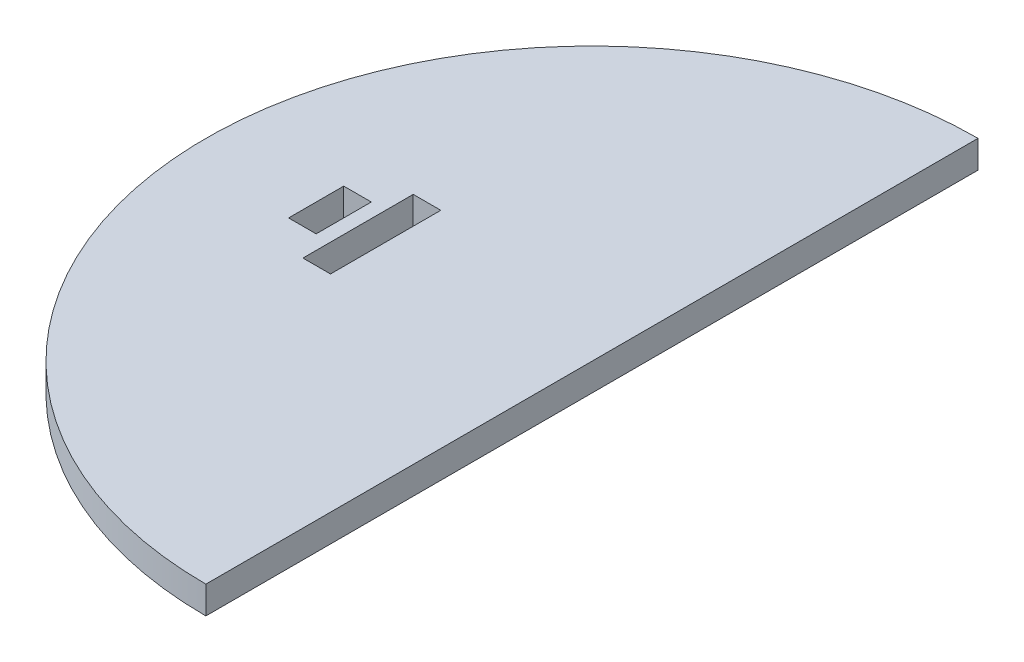
SolidWorks part; units mm, degrees
ref_plane "Front Plane" through (0, 0, 0) normal (0, 0, 1) x (1, 0, 0)
ref_plane "Top Plane" through (0, 0, 0) normal (0, 1, 0) x (1, 0, 0)
ref_plane "Right Plane" through (0, 0, 0) normal (1, 0, 0) x (0, 0, -1)
sketch "Sketch1" plane through (0, 0, 0) normal (0, 1, 0) x (1, 0, 0)
  line L0 (0, 70) -> (0, -70)
  line L2 (-50, -5) -> (-45, -5)
  line L3 (-50, -5) -> (-50, 5)
  line L4 (-50, 5) -> (-45, 5)
  line L5 (-45, -5) -> (-45, 5)
  line L6 (-50, -5) -> (-45, 5) construction
  line L7 (-50, 5) -> (-45, -5) construction
  arc A0 (0, 70) -> (0, -70) centre (0, 0) ccw
  point P4 (-47.5, 0)
  dimension "D1" = 70
  dimension "D5" = 140
  dimension "D2" = 10
  dimension "D3" = 5
  dimension "D4" = 45
extrude "Boss-Extrude1" add sketch "Sketch1" along normal blind 5 contours L0 A0 | L3 L2 L5 L4
sketch "Sketch2" plane through (0, 5, 0) normal (0, 1, 0) x (1, 0, 0)
  line L0 (0, 0) -> (-37.4, 0)
  line L1 (0, 70) -> (0, -70) construction
  line L2 (-37.4, 0) -> (-37.4, -10)
  line L3 (-37.4, -10) -> (-42.4, -10)
  line L4 (-42.4, -10) -> (-42.4, 10)
  line L5 (-42.4, 10) -> (-37.4, 10)
  line L6 (-37.4, 10) -> (-37.4, 0)
  dimension "D1" = 37.4
  dimension "D2" = 5
  dimension "D3" = 20
  dimension "D4" = 10
extrude "Cut-Extrude1" cut sketch "Sketch2" against normal blind 10 contours L2 L3 L4 L5 L6
